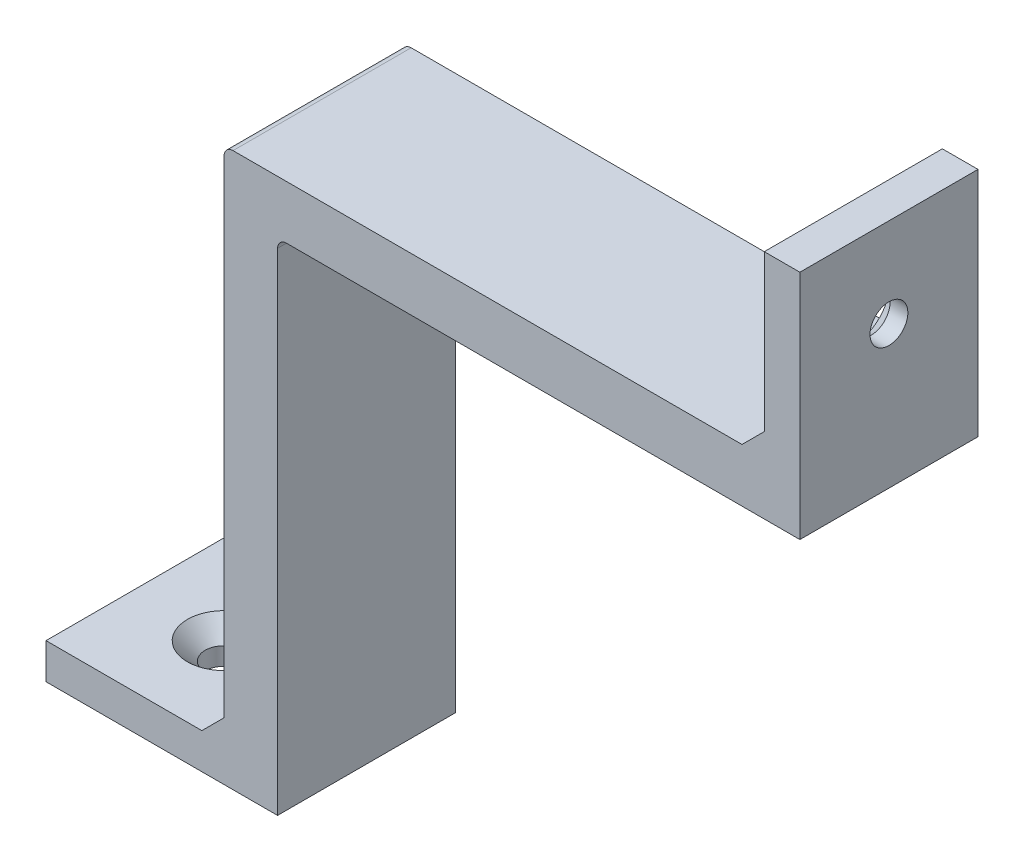
SolidWorks part; units mm, degrees
ref_plane "Front Plane" through (0, 0, 0) normal (0, 0, 1) x (1, 0, 0)
ref_plane "Top Plane" through (0, 0, 0) normal (0, 1, 0) x (1, 0, 0)
ref_plane "Right Plane" through (0, 0, 0) normal (1, 0, 0) x (0, 0, -1)
sketch "Sketch1" plane through (0, 0, 0) normal (0, 0, 1) x (1, 0, 0)
  line L0 (-26.5825, -13.85) -> (49973.4175, -13.85) construction
  line L1 (0, 0) -> (42.3, 0) construction
  line L2 (0, 0) -> (0, 42.3) construction
  line L3 (0, 42.3) -> (42.3, 42.3) construction
  line L4 (42.3, 0) -> (42.3, 42.3) construction
  line L5 (58.65, -3.8647) -> (58.65, 49996.1353) construction
  line L6 (58.65, 42.3) -> (0, 42.3)
  line L7 (0, 42.3) -> (0, -13.85)
  line L8 (58.65, 48.3) -> (-6, 48.3)
  line L9 (-6, 48.3) -> (-6, -13.85)
  line L10 (-6, -13.85) -> (0, -13.85)
  line L11 (58.65, 48.3) -> (58.65, 42.3)
  line L12 (-6, -13.85) -> (-26, -13.85)
  line L13 (-26, -13.85) -> (-26, -9.85)
  line L14 (-26, -9.85) -> (-6, -9.85)
  line L15 (58.65, 48.3) -> (58.65, 68.3)
  line L16 (58.65, 68.3) -> (54.65, 68.3)
  line L17 (54.65, 68.3) -> (54.65, 48.3)
  point P19 (-31, -4.9537)
  dimension "D1" = 42.3
  dimension "D2" = 13.85
  dimension "D3" = 16.35
  dimension "D5" = 20
  dimension "D6" = 4
  dimension "D4" = 6
extrude "Boss-Extrude1" add sketch "Sketch1" along normal blind 20 contours L14 L13 L12 L9 | L11 L8 L9 L10 L7 L6 | L16 L17 L8 L15
sketch "Sketch2" plane through (0, -9.85, 0) normal (0, 1, 0) x (1, 0, 0)
  line L0 (-26, 0) -> (-6, -20) construction
  line L4 (-6, 0) -> (-26, 0)
  line L5 (-26, 0) -> (-26, -20)
  line L6 (-26, -20) -> (-6, -20)
  line L7 (-6, -20) -> (-6, 0)
  line L8 (-6, 0) -> (-26, 0) construction
  line L9 (-26, 0) -> (-26, -20) construction
  line L10 (-26, -20) -> (-6, -20) construction
  line L11 (-6, -20) -> (-6, 0) construction
  circle A0 centre (-16, -10) radius 2.125
  dimension "D2" = 4.25
  dimension "D1" = 0
extrude "Cut-Extrude1" cut sketch "Sketch2" against normal through all
sketch "Sketch3" plane through (54.65, 0, 0) normal (-1, 0, 0) x (0, 0, 1)
  line L0 (0, 48.3) -> (20, 68.3) construction
  line L4 (0, 68.3) -> (0, 48.3)
  line L5 (0, 48.3) -> (20, 48.3)
  line L6 (20, 48.3) -> (20, 68.3)
  line L7 (20, 68.3) -> (0, 68.3)
  line L8 (0, 68.3) -> (0, 48.3) construction
  line L9 (0, 48.3) -> (20, 48.3) construction
  line L10 (20, 48.3) -> (20, 68.3) construction
  line L11 (20, 68.3) -> (0, 68.3) construction
  circle A0 centre (10, 58.3) radius 2.125
  dimension "D2" = 4.25
  dimension "D1" = 0
extrude "Cut-Extrude2" cut sketch "Sketch3" against normal through all
chamfer "Chamfer1" distance 2 angle 45 2 edges at (-18.125, -9.85, 10) (54.65, 56.175, 10)
chamfer "Chamfer2" distance 2.5 angle 45 2 edges at (54.65, 48.3, 10) (-6, -9.85, 10)
fillet "Fillet1" radius 1 2 edges at (0, 42.3, 10) (-6, 48.3, 10)
